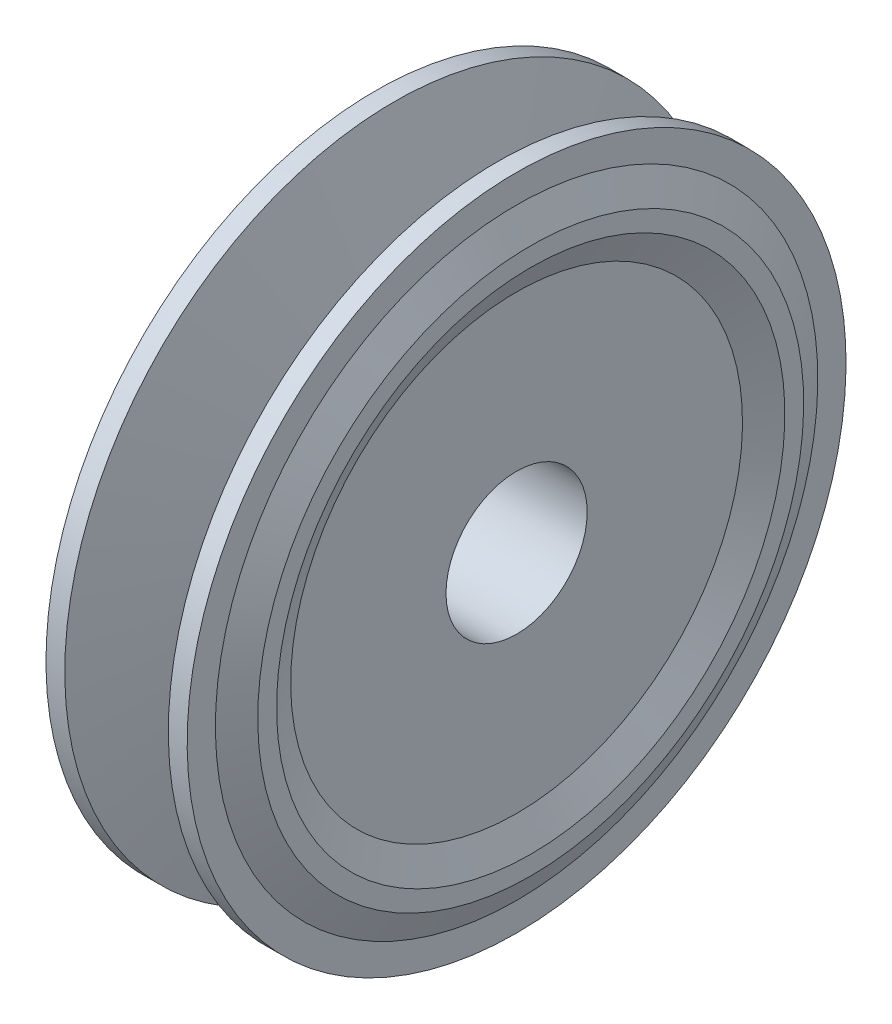
SolidWorks part; units mm, degrees
ref_plane "Спереди" through (0, 0, 0) normal (0, 0, 1) x (1, 0, 0)
ref_plane "Сверху" through (0, 0, 0) normal (0, 1, 0) x (1, 0, 0)
ref_plane "Справа" through (0, 0, 0) normal (1, 0, 0) x (0, 0, -1)
sketch "Эскиз1" plane through (0, 0, 0) normal (0, 0, 1) x (1, 0, 0)
  line L0 (5.5, 35) -> (7.5, 35)
  line L1 (7.5, 35) -> (7.5, 32)
  line L2 (5.5, 35) -> (1.75, 18)
  line L3 (1.75, 18) -> (-1.75, 18)
  line L4 (-1.75, 18) -> (-5.5, 35)
  line L5 (-5.5, 35) -> (-7.5, 35)
  line L6 (-7.5, 35) -> (-7.5, 32)
  line L7 (-7.5, 32) -> (-9, 29)
  line L8 (-9, 29) -> (-9, 26.9994)
  line L9 (9, 26.9994) -> (7.5, 24)
  line L10 (7.5, 24) -> (7.5, 0)
  line L11 (-9, 26.9994) -> (-7.5, 24)
  line L12 (-7.5, 24) -> (-7.5, 0)
  line L17 (7.5, 32) -> (9, 29)
  line L18 (9, 29) -> (9, 26.9994)
  line L20 (0, 18) -> (0, -18) construction
  line L21 (0, 0) -> (18, 0) construction
  line L22 (-7.5, 0) -> (7.5, 0)
  point P24 (9, 0)
  point P26 (-9, 0)
  dimension "D2" = 18
  dimension "D3" = 9
  dimension "D4" = 3.5
  dimension "D5" = 18
  dimension "D6" = 35
  dimension "D8" = 2
  dimension "D9" = 3
  dimension "D10" = 5.5
  dimension "D11" = 5.5
  dimension "D12" = 24
  dimension "D13" = 153.435
  dimension "D14" = 153.43
  dimension "D15" = 2.0006
  dimension "D16" = 3
revolve "Повернуть4" add sketch "Эскиз1" angle 360 about L21
sketch "Эскиз2" plane through (9, 0, 0) normal (1, 0, 0) x (0, 0, -1)
  circle A0 centre (0, 0) radius 7.5
  dimension "D1" = 15
extrude "Вырез-Вытянуть1" cut sketch "Эскиз2" against normal through all
